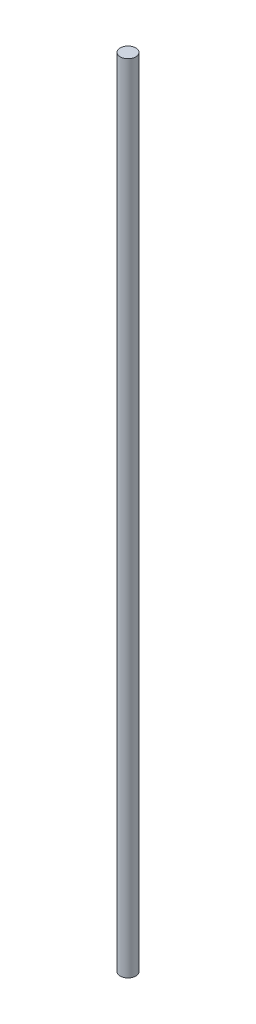
SolidWorks part; units mm, degrees
ref_plane "Спереди" through (0, 0, 0) normal (0, 0, 1) x (1, 0, 0)
ref_plane "Сверху" through (0, 0, 0) normal (0, 1, 0) x (1, 0, 0)
ref_plane "Справа" through (0, 0, 0) normal (1, 0, 0) x (0, 0, -1)
sketch "Эскиз1" plane through (0, 0, 0) normal (0, 1, 0) x (1, 0, 0)
  circle A0 centre (0, 0) radius 3
extrude "Вытянуть1" add sketch "Эскиз1" along normal blind 307
